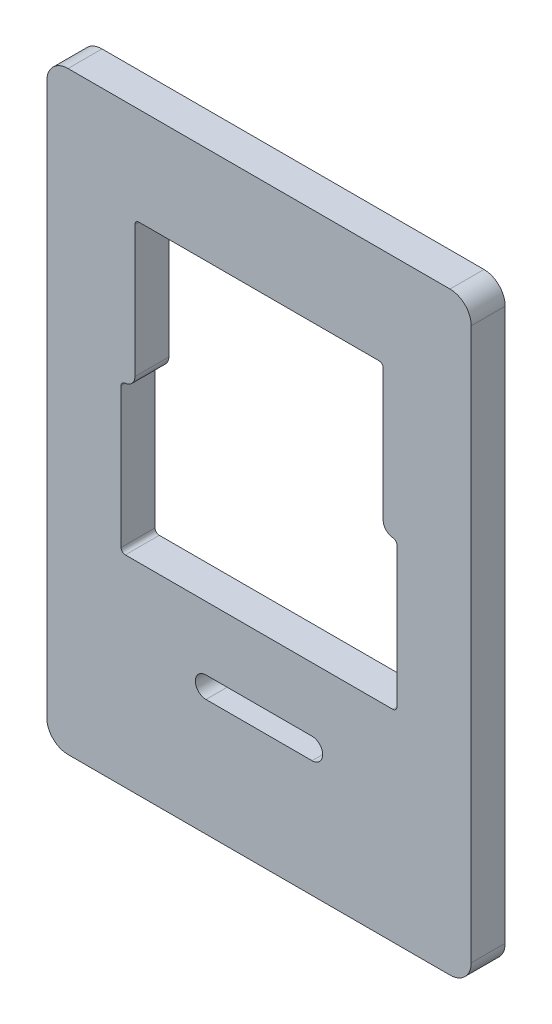
SolidWorks part; units mm, degrees
material "Silicon Rubber"
ref_plane "Front Plane" through (0, 0, 0) normal (0, 0, 1) x (1, 0, 0)
ref_plane "Top Plane" through (0, 0, 0) normal (0, 1, 0) x (1, 0, 0)
ref_plane "Right Plane" through (0, 0, 0) normal (1, 0, 0) x (0, 0, -1)
sketch "MainBodyS" plane through (0, 0, 0) normal (0, 0, 1) x (1, 0, 0)
  line L1 (-10, 14) -> (10, 14)
  line L2 (-10, 14) -> (-10, -14)
  line L3 (-10, -14) -> (10, -14)
  line L4 (10, 14) -> (10, -14)
  line L5 (-10, 14) -> (10, -14) construction
  line L6 (-10, -14) -> (10, 14) construction
  point P0 (0, 0)
  dimension "Width" = 20
  dimension "Height" = 28
extrude "MAIN BODY" add sketch "MainBodyS" against normal blind 1.6
sketch "GroundCutS" plane through (0, 0, 0) normal (0, 0, 1) x (1, 0, 0)
  line L0 (-2.5, -8) -> (2.5, -8) construction
  line L1 (-2.5, -7.5) -> (2.5, -7.5)
  line L2 (-2.5, -8.5) -> (2.5, -8.5)
  line L3 (0, -14) -> (0, -8) construction
  line L4 (-10, -14) -> (10, -14) construction
  arc A0 (-2.5, -7.5) -> (-2.5, -8.5) centre (-2.5, -8) ccw
  arc A1 (2.5, -8.5) -> (2.5, -7.5) centre (2.5, -8) ccw
  point P2 (0, -8)
  dimension "Height" = 1
  dimension "Width" = 5
  dimension "YLoc" = 6
extrude "GROUND CUT" cut sketch "GroundCutS" against normal through all
sketch "MidCutS" plane through (0, 0, 0) normal (0, 0, 1) x (1, 0, 0)
  line L0 (0, 0) -> (0, -1) construction
  line L1 (-6.5, 2.5) -> (6.5, 2.5)
  line L2 (-6.5, 2.5) -> (-6.5, -4.5)
  line L3 (-6.5, -4.5) -> (6.5, -4.5)
  line L4 (6.5, 2.5) -> (6.5, -4.5)
  line L5 (-6.5, 2.5) -> (6.5, -4.5) construction
  line L6 (-6.5, -4.5) -> (6.5, 2.5) construction
  line L7 (-10, 14) -> (-10, -14) construction
  arc A0 (-2.5, -7.5) -> (-2.5, -8.5) centre (-2.5, -8) ccw construction
  point P0 (0, -1)
  dimension "WidthControl" = 3.5
  dimension "Height" = 7
  dimension "RefWidth" = 13
  dimension "YLoc" = 3.5
extrude "MID CUT" cut sketch "MidCutS" against normal through all
sketch "TopPowerAccessCutS" plane through (0, 0, 0) normal (0, 0, 1) x (1, 0, 0)
  line L0 (6.5, 2.5) -> (-6.5, 2.5) construction
  line L1 (-5.85, 9.4) -> (5.85, 9.4)
  line L2 (-5.85, 9.4) -> (-5.85, 2.5)
  line L3 (-5.85, 2.5) -> (5.85, 2.5)
  line L4 (5.85, 9.4) -> (5.85, 2.5)
  line L5 (-5.85, 9.4) -> (5.85, 2.5) construction
  line L6 (-5.85, 2.5) -> (5.85, 9.4) construction
  line L8 (-6.5, 2.5) -> (-6.5, -4.5) construction
  line L10 (0, 0) -> (0, 5.95) construction
  line L11 (10, 14) -> (-10, 14) construction
  point P0 (0, 5.95)
  dimension "WidthControl" = 0.65
  dimension "HeightStart" = 4.6
extrude "TOP POWER ACCESS CUT" cut sketch "TopPowerAccessCutS" against normal through all
fillet "MC FILLET" radius 0.5 2 edges at (5.85, 2.5, -0.8) (-5.85, 2.5, -0.8)
fillet "ALL INNER CUTS FILLETS" radius 0.2 6 edges at (-6.5, -4.5, -0.8) (6.5, -4.5, -0.8) (6.5, 2.5, -0.8) (-6.5, 2.5, -0.8) (-5.85, 9.4, -0.8) (5.85, 9.4, -0.8)
fillet "OUTER FILLETS" radius 1 4 edges at (-10, -14, -0.8) (10, -14, -0.8) (10, 14, -0.8) (-10, 14, -0.8)
